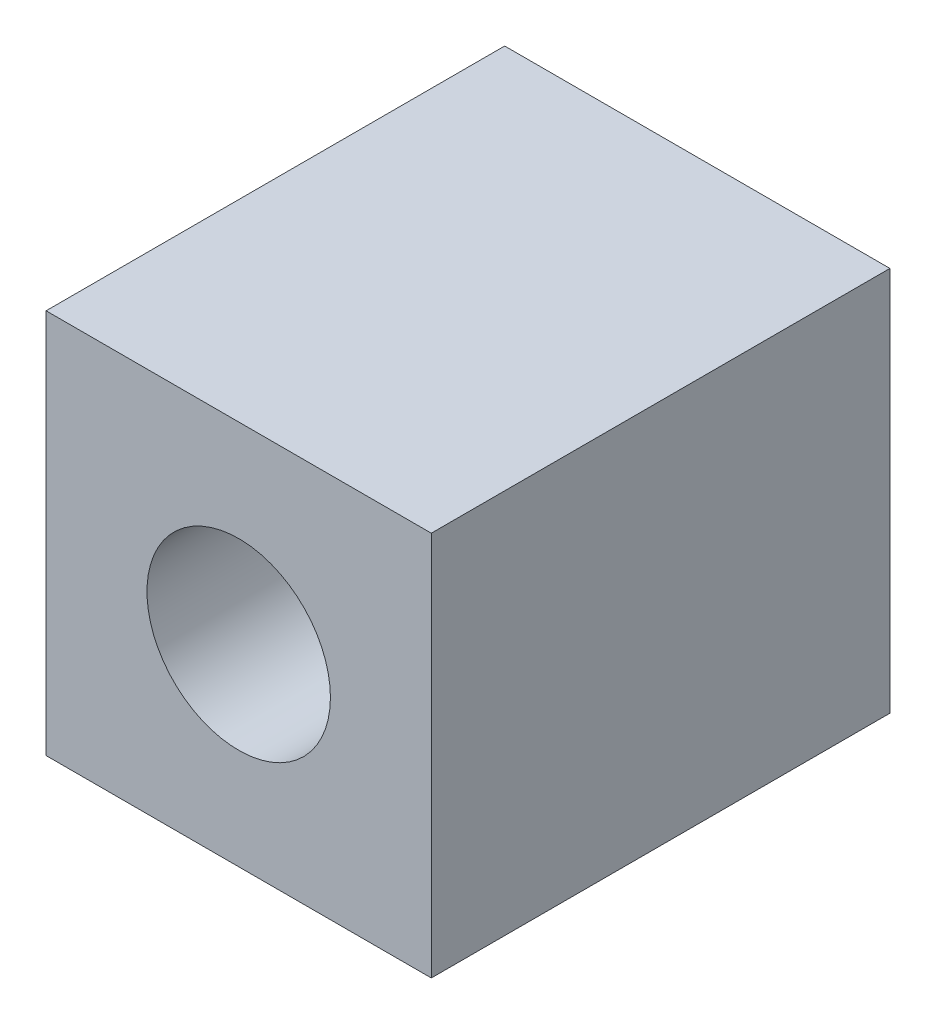
SolidWorks part; units mm, degrees
ref_plane "Plan de face" through (0, 0, 0) normal (0, 0, 1) x (1, 0, 0)
ref_plane "Plan de dessus" through (0, 0, 0) normal (0, 1, 0) x (1, 0, 0)
ref_plane "Plan de droite" through (0, 0, 0) normal (1, 0, 0) x (0, 0, -1)
sketch "Esquisse1" plane through (0, 0, 0) normal (0, 0, 1) x (1, 0, 0)
  line L1 (-21, -21) -> (21, -21)
  line L2 (-21, -21) -> (-21, 21)
  line L3 (-21, 21) -> (21, 21)
  line L4 (21, -21) -> (21, 21)
  line L5 (-21, -21) -> (21, 21) construction
  line L6 (-21, 21) -> (21, -21) construction
  point P0 (0, 0)
  dimension "D1" = 42
  dimension "D2" = 42
extrude "Boss.-Extru.1" add sketch "Esquisse1" along normal blind 50
sketch "Esquisse2" plane through (0, 0, 50) normal (0, 0, 1) x (1, 0, 0)
  circle A0 centre (0, 0) radius 10
  dimension "D1" = 20
extrude "Enlèv. mat.-Extru.1" cut sketch "Esquisse2" against normal through all
